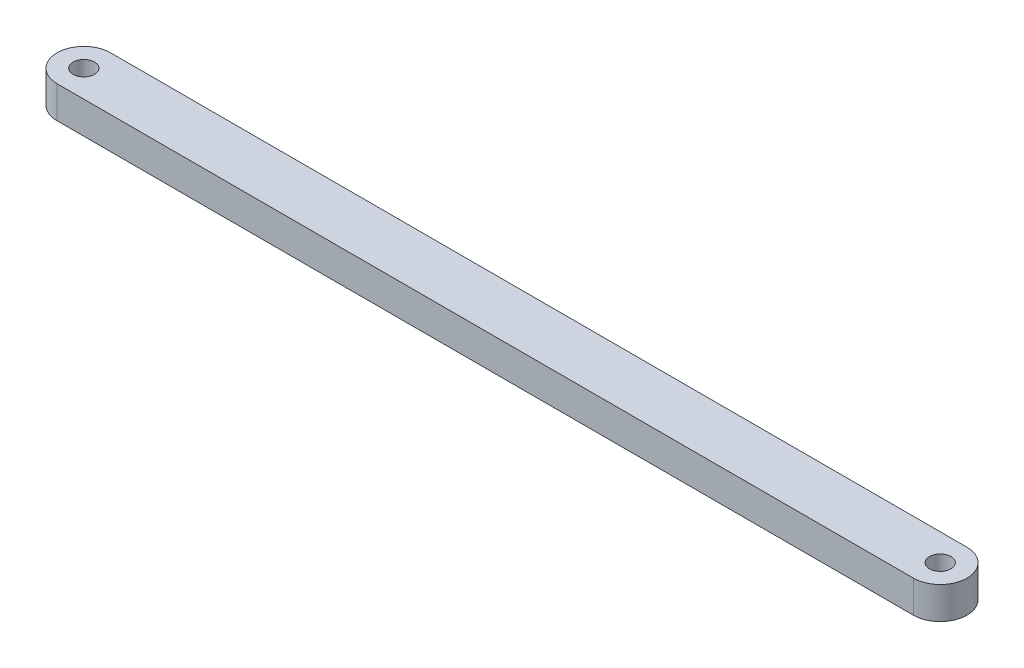
SolidWorks part; units mm, degrees
material "1060 Alloy"
ref_plane "Front Plane" through (0, 0, 0) normal (0, 0, 1) x (1, 0, 0)
ref_plane "Top Plane" through (0, 0, 0) normal (0, 1, 0) x (1, 0, 0)
ref_plane "Right Plane" through (0, 0, 0) normal (1, 0, 0) x (0, 0, -1)
sketch "Sketch1" plane through (0, 0, 0) normal (0, 1, 0) x (1, 0, 0)
  line L0 (0, 0) -> (-800, 0) construction
  line L1 (0, -25) -> (-800, -25)
  line L2 (0, 25) -> (-800, 25)
  arc A0 (0, -25) -> (0, 25) centre (0, 0) ccw
  arc A1 (-800, 25) -> (-800, -25) centre (-800, 0) ccw
  circle A2 centre (-800, 0) radius 10
  circle A3 centre (0, 0) radius 10
  point P3 (-400, 0)
  point P12 (0, 0)
  dimension "D1" = 20
  dimension "D2" = 20
  dimension "D3" = 50
  dimension "D4" = 800
extrude "Boss-Extrude1" add sketch "Sketch1" along normal blind 30
